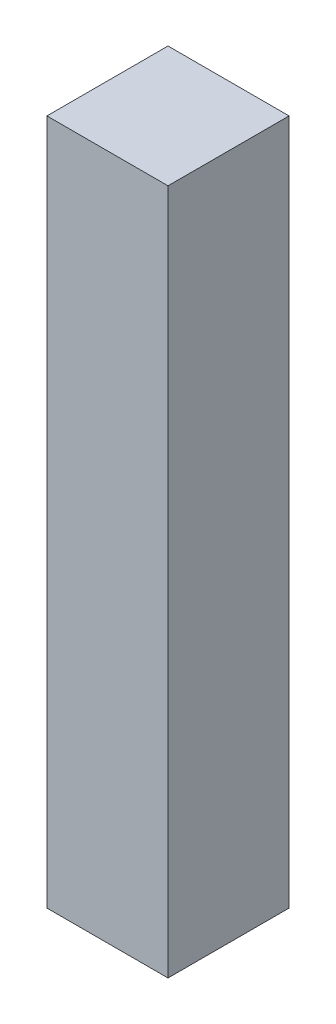
SolidWorks part; units mm, degrees
ref_plane "Front Plane" through (0, 0, 0) normal (0, 0, 1) x (1, 0, 0)
ref_plane "Top Plane" through (0, 0, 0) normal (0, 1, 0) x (1, 0, 0)
ref_plane "Right Plane" through (0, 0, 0) normal (1, 0, 0) x (0, 0, -1)
sketch "Sketch1" plane through (0, 0, 0) normal (0, 1, 0) x (1, 0, 0)
  line L1 (150, -150) -> (-150, -150)
  line L2 (150, -150) -> (150, 150)
  line L3 (150, 150) -> (-150, 150)
  line L4 (-150, -150) -> (-150, 150)
  line L5 (150, -150) -> (-150, 150) construction
  line L6 (150, 150) -> (-150, -150) construction
  point P0 (0, 0)
  dimension "D1" = 300
  dimension "D2" = 300
extrude "Boss-Extrude1" add sketch "Sketch1" along normal blind 1700
